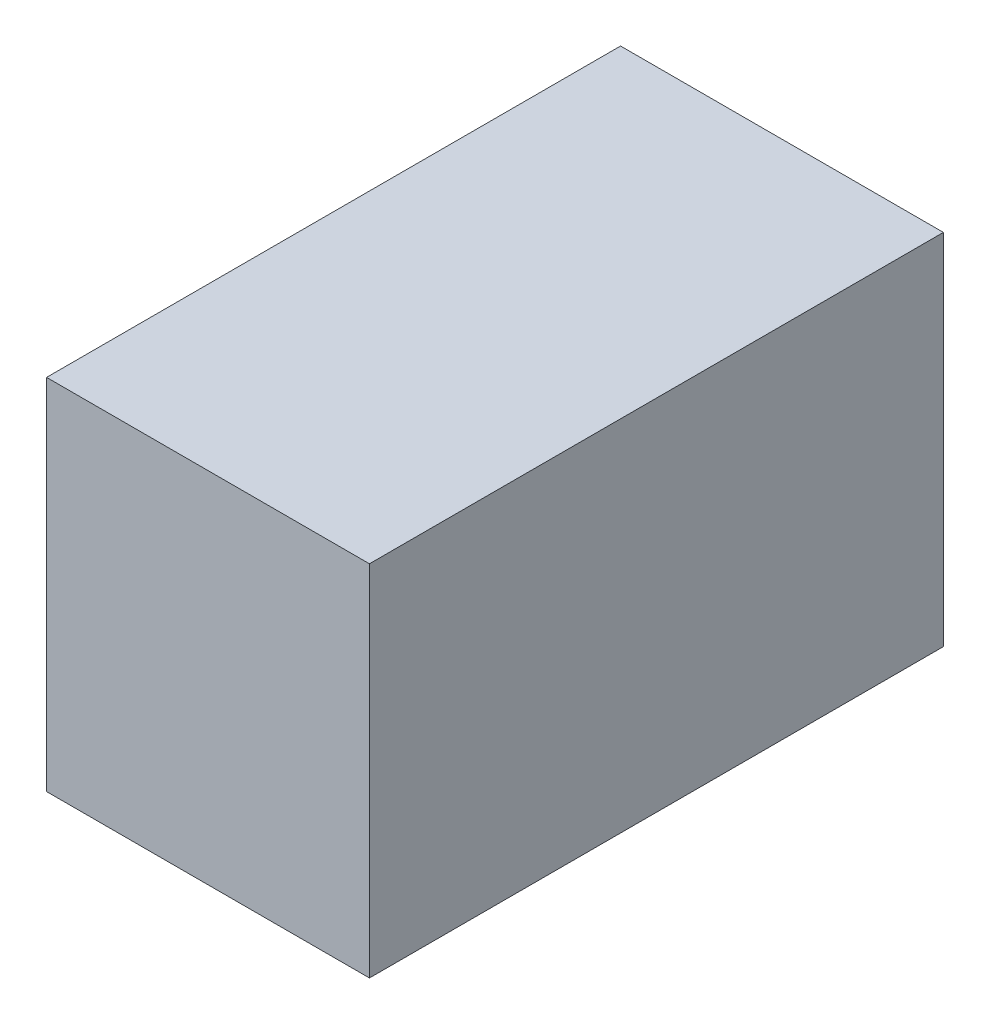
SolidWorks part; units mm, degrees
ref_plane "Front Plane" through (0, 0, 0) normal (0, 0, 1) x (1, 0, 0)
ref_plane "Top Plane" through (0, 0, 0) normal (0, 1, 0) x (1, 0, 0)
ref_plane "Right Plane" through (0, 0, 0) normal (1, 0, 0) x (0, 0, -1)
sketch "Sketch1" plane through (0, 0, 0) normal (0, 0, 1) x (1, 0, 0)
  line L1 (0, 0) -> (45, 0)
  line L2 (0, 0) -> (0, 50)
  line L3 (0, 50) -> (45, 50)
  line L4 (45, 0) -> (45, 50)
  dimension "D1" = 45
  dimension "D2" = 50
extrude "Boss-Extrude1" add sketch "Sketch1" along normal blind 80
